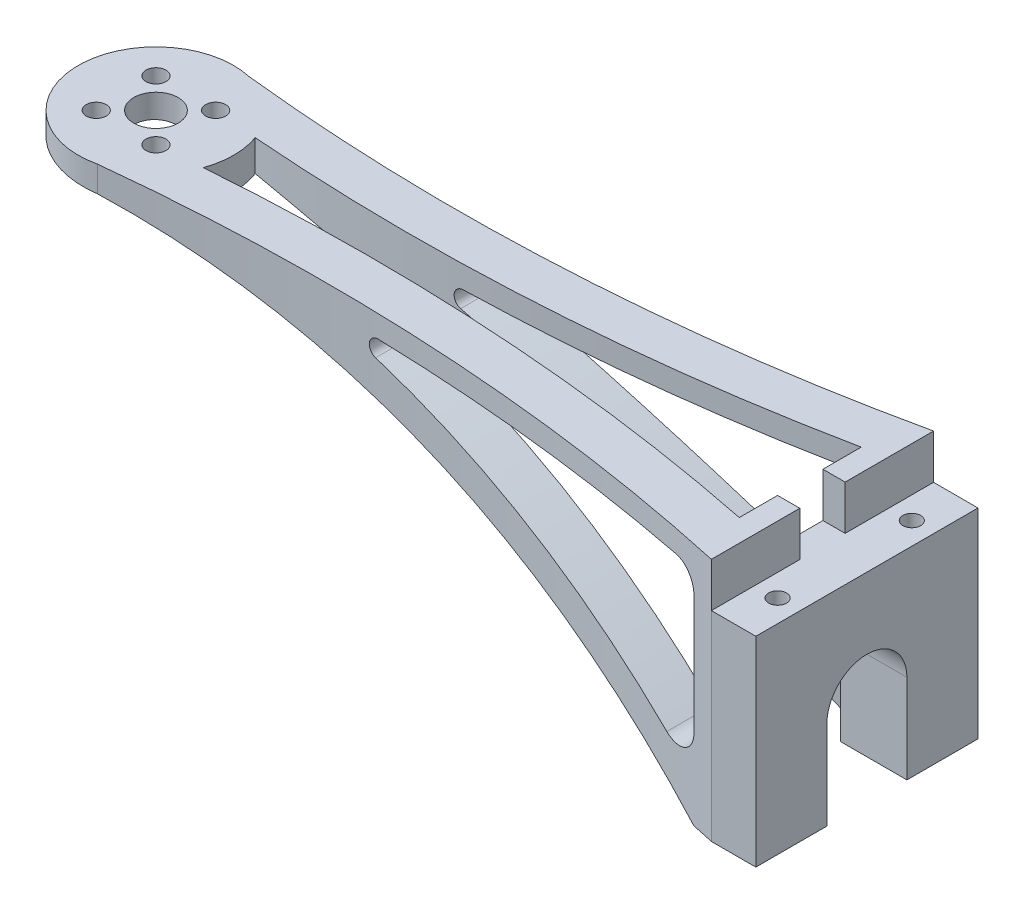
SolidWorks part; units mm, degrees
ref_plane "Plan de face" through (0, 0, 0) normal (0, 0, 1) x (1, 0, 0)
ref_plane "Plan de dessus" through (0, 0, 0) normal (0, 1, 0) x (1, 0, 0)
ref_plane "Plan de droite" through (0, 0, 0) normal (1, 0, 0) x (0, 0, -1)
sketch "Esquisse2" plane through (0, 0, 0) normal (0, 1, 0) x (1, 0, 0)
  line L8 (-160, 0) -> (0, 0) construction
  line L9 (-84.6875, -15) -> (-84.6875, 15) construction
  line L10 (-10, 25) -> (0, 25)
  line L11 (0, 25) -> (0, -25)
  line L12 (0, -25) -> (-10, -25)
  circle A0 centre (-160, 0) radius 17.5
  arc A1 (-10, 25) -> (-160, 17.5) centre (-107.3437, 468.125) cw
  arc A2 (-160, -17.5) -> (-10, -25) centre (-107.3437, -468.125) cw
  point P15 (-84.6875, 0)
  dimension "D4" = 35
  dimension "D1" = 50
  dimension "D2" = 30
  dimension "D3" = 160
  dimension "D5" = 10
extrude "Base" add sketch "Esquisse2" along normal blind 5
sketch "Esquisse6" plane through (0, 0, 0) normal (0, 0, 1) x (1, 0, 0)
  line L0 (0, 0) -> (0, -50)
  line L1 (0, -50) -> (-15, -50)
  line L2 (0, 0) -> (-15, 0)
  line L3 (-15, -40.9837) -> (-15, 0)
  line L6 (-111.2264, 0) -> (-177.5, 0)
  arc A0 (-177.5, 0) -> (-15, -50) centre (-177.5, -289.0625) cw
  arc A2 (-111.2264, 0) -> (-15, -40.9837) centre (-177.5, -289.0625) cw
  dimension "D3" = 7.5
  dimension "D1" = 15
  dimension "D2" = 50
extrude "Support" add sketch "Esquisse6" along normal blind 30 and the other way blind 30
sketch "Esquisse7" plane through (0, 0, 0) normal (0, 1, 0) x (1, 0, 0)
  line L1 (-10, -25) -> (0, -25)
  line L5 (-10, -25) -> (0, -25)
  line L6 (0, -25) -> (0, 25)
  line L7 (0, -25) -> (0, 25)
  line L8 (0, 25) -> (-10, 25)
  line L9 (0, 25) -> (-10, 25)
  arc A3 (-156.1123, 17.0627) -> (-10, 25) centre (-107.3437, 468.125) ccw
  arc A4 (-156.1123, 17.0627) -> (-156.1123, -17.0627) centre (-160, 0) ccw
  arc A5 (-10, -25) -> (-156.1123, -17.0627) centre (-107.3437, -468.125) ccw
  arc A6 (-156.1123, 17.0627) -> (-10, 25) centre (-107.3437, 468.125) ccw
  arc A7 (-156.1123, 17.0627) -> (-156.1123, -17.0627) centre (-160, 0) ccw
  arc A8 (-10, -25) -> (-156.1123, -17.0627) centre (-107.3437, -468.125) ccw
  dimension "D1" = 0
extrude "Ajustement" cut sketch "Esquisse7" against normal through all flip side to cut
sketch "Esquisse9" plane through (0, 5, 0) normal (0, 1, 0) x (1, 0, 0)
  line L1 (0, 25) -> (0, -25) construction
  line L3 (-15, -13.7221) -> (-15, 13.7221)
  arc A0 (-156.1123, 17.0627) -> (-156.1123, -17.0627) centre (-160, 0) ccw construction
  arc A1 (-156.1123, 17.0627) -> (-10, 25) centre (-107.3437, 468.125) ccw construction
  arc A3 (-143.5054, 5.8462) -> (-143.5054, -5.8462) centre (-160, 0) cw
  arc A4 (-15, -23.9311) -> (-111.2264, -14.4506) centre (-107.3437, -468.125) ccw construction
  arc A5 (-15, -23.9311) -> (-156.1123, -17.0627) centre (-107.3437, -468.125) ccw construction
  arc A9 (-143.5054, 5.8462) -> (-15, 13.7221) centre (-107.3437, 468.125) ccw
  arc A11 (-15, -13.7221) -> (-143.5054, -5.8462) centre (-107.3437, -468.125) ccw
  dimension "D1" = 10
  dimension "D2" = 15
extrude "Trou_centre" cut sketch "Esquisse9" against normal through all
sketch "Esquisse11" plane through (0, 5, 0) normal (0, 1, 0) x (1, 0, 0)
  line L0 (-166.7175, 6.7175) -> (-153.2825, -6.7175) construction
  line L1 (-153.2825, 6.7175) -> (-166.7175, -6.7175) construction
  line L2 (-153.2825, 6.7175) -> (-153.2825, -6.7175) construction
  circle A0 centre (-160, 0) radius 9.5 construction
  circle A1 centre (-153.2825, 6.7175) radius 2.25
  circle A2 centre (-153.2825, -6.7175) radius 2.25
  circle A3 centre (-166.7175, -6.7175) radius 2.25
  circle A4 centre (-166.7175, 6.7175) radius 2.25
  circle A5 centre (-160, 0) radius 5
  dimension "D1" = 19
  dimension "D2" = 4.5
  dimension "D3" = 10
extrude "Trou_moteur" cut sketch "Esquisse11" against normal through all
fillet "Congé2" radius 5 4 edges at (-15, -40.9837, 18.8266) (-15, -40.9837, -18.8266) (-15, 0, -18.8266) (-15, 0, 18.8266)
fillet "Congé3" radius 2 2 edges at (-111.2264, 0, -9.4504) (-111.2264, 0, 9.4504)
sketch "Esquisse12" plane through (0, 5, 0) normal (0, 1, 0) x (1, 0, 0)
  line L1 (-10, -5.1) -> (-15, -5.1)
  line L3 (-10, 5.1) -> (-15, 5.1)
  line L4 (-15, -5.1) -> (-15, 5.1)
  line L5 (-15, -13.7221) -> (-15, 13.7221) construction
  line L6 (-10, -25) -> (-10, -5.1)
  line L7 (-10, 5.1) -> (-10, 25)
  line L8 (-10, -25) -> (0, -25)
  line L10 (0, 0) -> (-15, 0) construction
  line L14 (-10, -25) -> (0, -25)
  line L15 (0, -25) -> (0, 25)
  line L16 (0, -25) -> (0, 25)
  line L17 (0, 25) -> (-10, 25)
  line L18 (0, 25) -> (-10, 25)
  arc A4 (-156.1123, 17.0627) -> (-10, 25) centre (-107.3437, 468.125) ccw
  arc A5 (-156.1123, 17.0627) -> (-156.1123, -17.0627) centre (-160, 0) ccw
  arc A6 (-10, -25) -> (-156.1123, -17.0627) centre (-107.3437, -468.125) ccw
  arc A8 (-156.1123, 17.0627) -> (-156.1123, -17.0627) centre (-160, 0) ccw
  dimension "D2" = 0
  dimension "D1" = 10.2
extrude "Trou_support" cut sketch "Esquisse12" against normal blind 10
sketch "Esquisse13" plane through (0, -5, 0) normal (0, 1, 0) x (1, 0, 0)
  line L0 (-10, -25) -> (0, -25) construction
  line L5 (-5, -25) -> (-5, 25) construction
  line L6 (-10, -5.1) -> (-15, -5.1) construction
  line L7 (-10, 5.1) -> (-15, 5.1) construction
  line L8 (0, 25) -> (-10, 25) construction
  circle A2 centre (-5, -15.1) radius 2
  circle A3 centre (-5, 15.1) radius 2
  point P23 (-3, 15.1)
  dimension "D1" = 4
  dimension "D2" = 10
  dimension "D3" = 10
extrude "Insert_haut" cut sketch "Esquisse13" against normal blind 7
sketch "Esquisse15" plane through (0, 0, 0) normal (1, 0, 0) x (0, 0, -1)
  line L0 (-9, -50) -> (-9, -30)
  line L1 (25, -50) -> (-25, -50) construction
  line L2 (9, -30) -> (9, -50)
  line L3 (-25, -5) -> (-25, -50) construction
  line L4 (25, -5) -> (25, -50) construction
  line L5 (-9, -50) -> (9, -50)
  arc A0 (-9, -30) -> (9, -30) centre (0, -30) cw
  dimension "D1" = 16
  dimension "D2" = 16
  dimension "D3" = 20
extrude "Pont" cut sketch "Esquisse15" against normal up to next and the other way through all
sketch "Esquisse14" plane through (0, -50, 0) normal (0, -1, 0) x (1, 0, 0)
  line L0 (0, -25) -> (-10, -25) construction
  line L2 (-7.5, -25) -> (-7.5, -9) construction
  line L4 (0, -9) -> (-15, -9) construction
  line L5 (-7.5, 9) -> (-7.5, 25) construction
  line L6 (-15, 9) -> (0, 9) construction
  line L7 (-10, 25) -> (0, 25) construction
  circle A4 centre (-7.5, 17) radius 2
  circle A5 centre (-7.5, -17) radius 2
  dimension "D3" = 4
extrude "Insert_bas" cut sketch "Esquisse14" against normal blind 7
